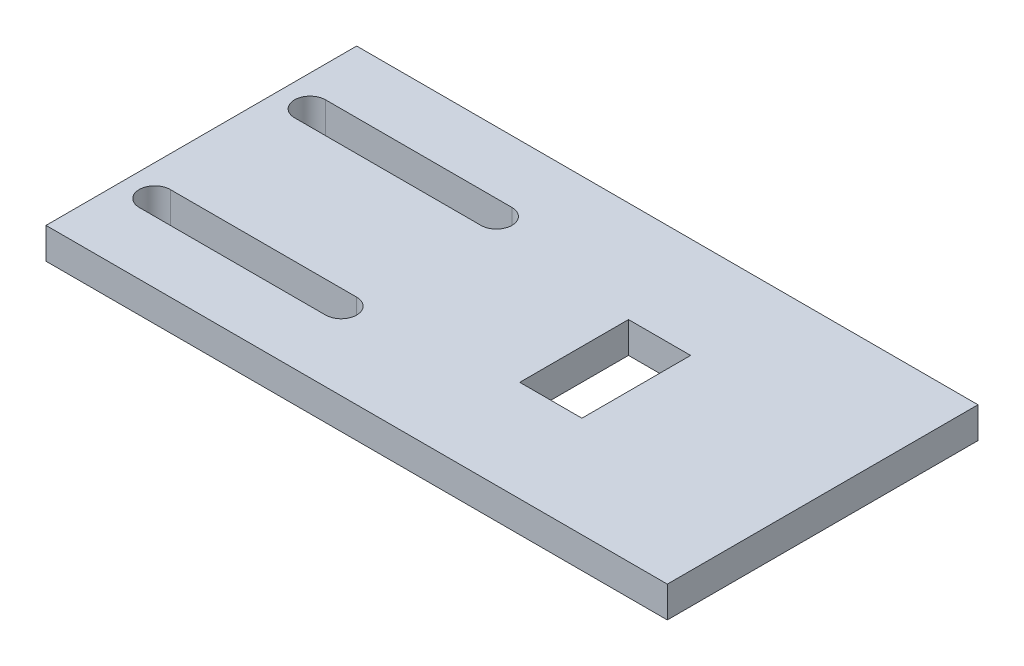
SolidWorks part; units mm, degrees
ref_plane "Front Plane" through (0, 0, 0) normal (0, 0, 1) x (1, 0, 0)
ref_plane "Top Plane" through (0, 0, 0) normal (0, 1, 0) x (1, 0, 0)
ref_plane "Right Plane" through (0, 0, 0) normal (1, 0, 0) x (0, 0, -1)
sketch "Sketch2" plane through (0, 0, 0) normal (0, 1, 0) x (1, 0, 0)
  line L1 (-50, 25) -> (50, 25)
  line L2 (-50, 25) -> (-50, -25)
  line L3 (-50, -25) -> (50, -25)
  line L4 (50, 25) -> (50, -25)
  line L5 (-50, 25) -> (50, -25) construction
  line L6 (-50, -25) -> (50, 25) construction
  point P0 (0, 0)
  dimension "D1" = 50
  dimension "D2" = 100
extrude "Boss-Extrude1" add sketch "Sketch2" along normal blind 5
sketch "Sketch3" plane through (0, 5, 0) normal (0, 1, 0) x (1, 0, 0)
  line L0 (0, 0) -> (15, 0) construction
  line L2 (10, 8.75) -> (20, 8.75)
  line L3 (10, 8.75) -> (10, -8.75)
  line L4 (10, -8.75) -> (20, -8.75)
  line L5 (20, 8.75) -> (20, -8.75)
  line L6 (10, 8.75) -> (20, -8.75) construction
  line L7 (10, -8.75) -> (20, 8.75) construction
  dimension "D1" = 15
  dimension "D2" = 10
  dimension "D3" = 17.5
extrude "Cut-Extrude1" cut sketch "Sketch3" against normal blind 7.5
sketch "Sketch4" plane through (0, 5, 0) normal (0, 1, 0) x (1, 0, 0)
  line L0 (-45, 12.5) -> (-15, 12.5) construction
  line L1 (-45, 15) -> (-15, 15)
  line L2 (-45, 10) -> (-15, 10)
  line L3 (-50, 25) -> (-50, -25) construction
  line L4 (50, 25) -> (-50, 25) construction
  line L5 (-45, -15) -> (-15, -15)
  line L6 (-45, -10) -> (-15, -10)
  line L7 (-45, -12.5) -> (-15, -12.5) construction
  arc A0 (-45, 15) -> (-45, 10) centre (-45, 12.5) ccw
  arc A1 (-15, 10) -> (-15, 15) centre (-15, 12.5) ccw
  arc A2 (-45, -10) -> (-45, -15) centre (-45, -12.5) ccw
  arc A3 (-15, -15) -> (-15, -10) centre (-15, -12.5) ccw
  point P2 (-30, 12.5)
  point P14 (-30, -12.5)
  dimension "D1" = 5
  dimension "D2" = 5
  dimension "D3" = 10
  dimension "D5" = 30
  dimension "D4" = 2
extrude "Cut-Extrude2" cut sketch "Sketch4" against normal blind 7.5
